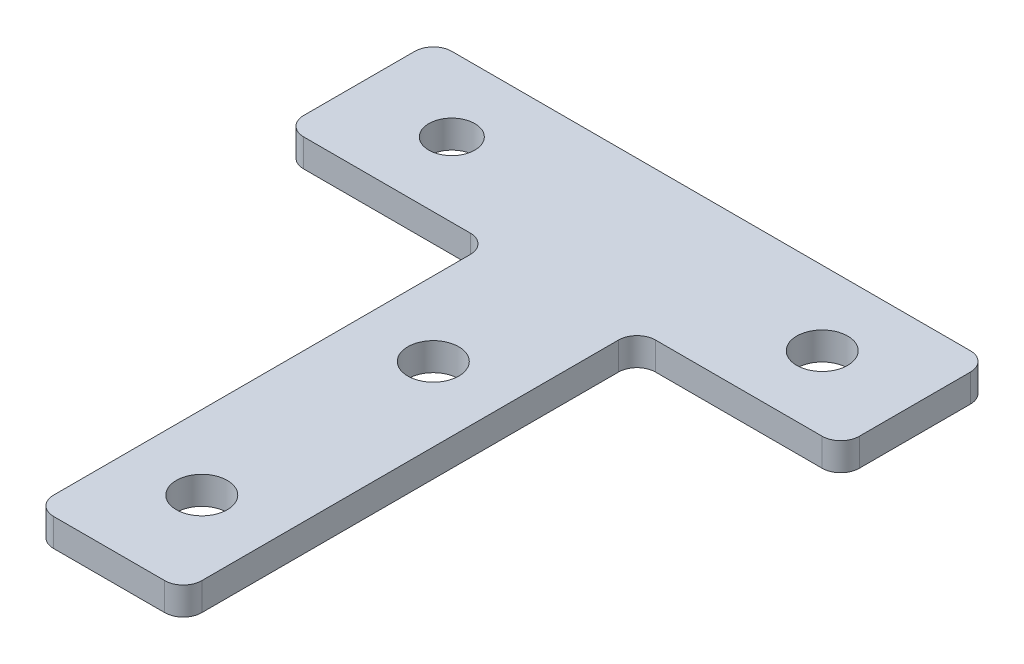
SolidWorks part; units mm, degrees
ref_plane "前视基准面" through (0, 0, 0) normal (0, 0, 1) x (1, 0, 0)
ref_plane "上视基准面" through (0, 0, 0) normal (0, 1, 0) x (1, 0, 0)
ref_plane "右视基准面" through (0, 0, 0) normal (1, 0, 0) x (0, 0, -1)
other "Configuration Table"
sketch "草图1" plane through (0, 0, 0) normal (0, 1, 0) x (1, 0, 0)
  line L0 (0, -2) -> (0, -14)
  line L1 (2, -16) -> (20, -16)
  line L2 (22, -18) -> (22, -63)
  line L3 (24, -65) -> (36, -65)
  line L4 (38, -63) -> (38, -18)
  line L5 (40, -16) -> (58, -16)
  line L6 (60, -14) -> (60, -2)
  line L7 (58, 0) -> (2, 0)
  line L8 (-1000, -8) -> (49000, -8) construction
  line L9 (30, -1000) -> (30, 49000) construction
  circle A0 centre (10, -8) radius 2.4855
  circle A1 centre (50, -8) radius 2.75
  circle A2 centre (30, -55) radius 2.75
  circle A3 centre (30, -30) radius 2.75
  arc A4 (20, -16) -> (22, -18) centre (20, -18) cw
  arc A5 (22, -63) -> (24, -65) centre (24, -63) ccw
  arc A6 (36, -65) -> (38, -63) centre (36, -63) ccw
  arc A7 (38, -18) -> (40, -16) centre (40, -18) cw
  arc A8 (58, -16) -> (60, -14) centre (58, -14) ccw
  arc A9 (60, -2) -> (58, 0) centre (58, -2) ccw
  arc A10 (0, -14) -> (2, -16) centre (2, -14) ccw
  arc A11 (0, -2) -> (2, 0) centre (2, -2) cw
  point P12 (0, -8)
  point P15 (30, 0)
  point P27 (22, -65)
  point P30 (38, -65)
  point P33 (38, -16)
  point P38 (60, 0)
  point P41 (0, -16)
  point P44 (0, 0)
  dimension "D7" = 5.5
  dimension "D10" = 5.5
  dimension "D11" = 5.5
  dimension "D13" = 2
  dimension "D1" = 60
  dimension "D2" = 16
  dimension "D3" = 16
  dimension "D4" = 49
  dimension "D5" = 65
  dimension "D6" = 10
  dimension "D8" = 40
  dimension "D9" = 25
  dimension "D12" = 10
extrude "凸台-拉伸1" add sketch "草图1" along normal blind 3
